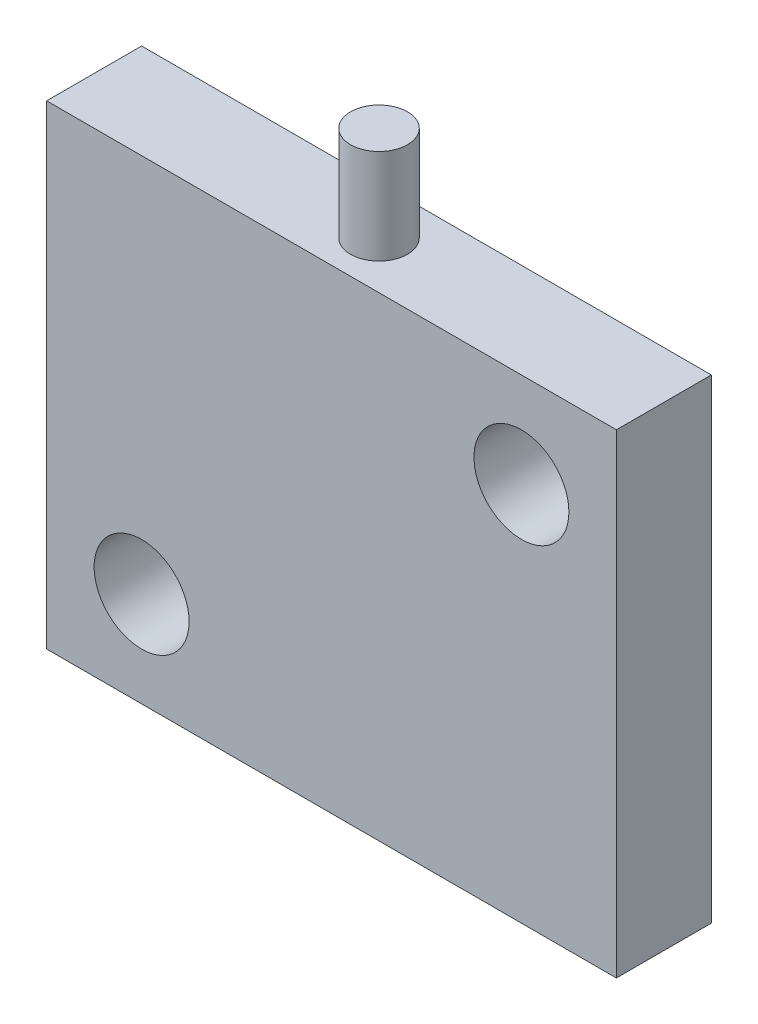
SolidWorks part; units mm, degrees
ref_plane "前视基准面" through (0, 0, 0) normal (0, 0, 1) x (1, 0, 0)
ref_plane "上视基准面" through (0, 0, 0) normal (0, 1, 0) x (1, 0, 0)
ref_plane "右视基准面" through (0, 0, 0) normal (1, 0, 0) x (0, 0, -1)
sketch "草图1" plane through (0, 0, 0) normal (0, 0, 1) x (1, 0, 0)
  line L1 (-30, 30) -> (30, 30)
  line L2 (-30, 30) -> (-30, -30)
  line L3 (-30, -30) -> (30, -30)
  line L4 (30, 30) -> (30, -30)
  line L5 (-30, 30) -> (30, -30) construction
  line L6 (-30, -30) -> (30, 30) construction
  point P0 (0, 0)
extrude "凸台-拉伸1" add sketch "草图1" along normal blind 10
sketch "草图2" plane through (0, 30, 0) normal (0, 1, 0) x (1, 0, 0)
  circle A0 centre (0, -5) radius 3
  line M2 (30, 0) -> (-30, 0)
  line M3 (-30, 0) -> (-30, -10)
  line M4 (-30, -10) -> (30, -10)
  line M5 (30, -10) -> (30, 0)
extrude "切除-拉伸1" cut sketch "草图2" against normal blind 10 contours A0 M5 M2 M3 M4
sketch "草图3" plane through (0, 0, 10) normal (0, 0, 1) x (1, 0, 0)
  circle A0 centre (-20, -20) radius 5
  circle A1 centre (20, 10) radius 5
extrude "切除-拉伸2" cut sketch "草图3" against normal through all contours A1 | A0
